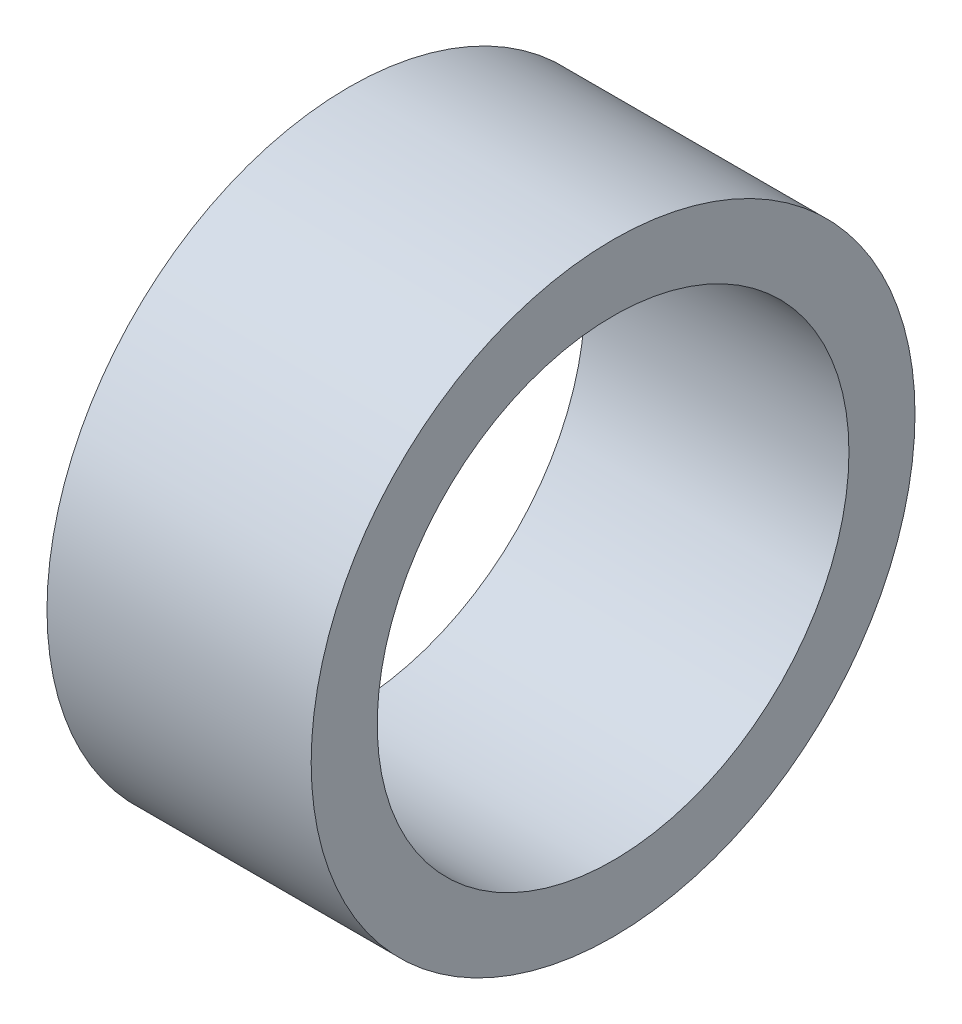
SolidWorks part; units mm, degrees
ref_plane "正面" through (0, 0, 0) normal (0, 0, 1) x (1, 0, 0)
ref_plane "平面" through (0, 0, 0) normal (0, 1, 0) x (1, 0, 0)
ref_plane "右側面" through (0, 0, 0) normal (1, 0, 0) x (0, 0, -1)
sketch "ｽｹｯﾁ1" plane through (0, 0, 0) normal (1, 0, 0) x (0, 0, -1)
  circle A0 centre (0, 0) radius 6.25
  circle A1 centre (0, 0) radius 8
  dimension "D1" = 12.5
  dimension "D2" = 16
extrude "ﾎﾞｽ - 押し出し1" add sketch "ｽｹｯﾁ1" along normal blind 7
equation "\"長さ\"= 7"
equation "\"D1@ﾎﾞｽ - 押し出し1\"=\"長さ\""
